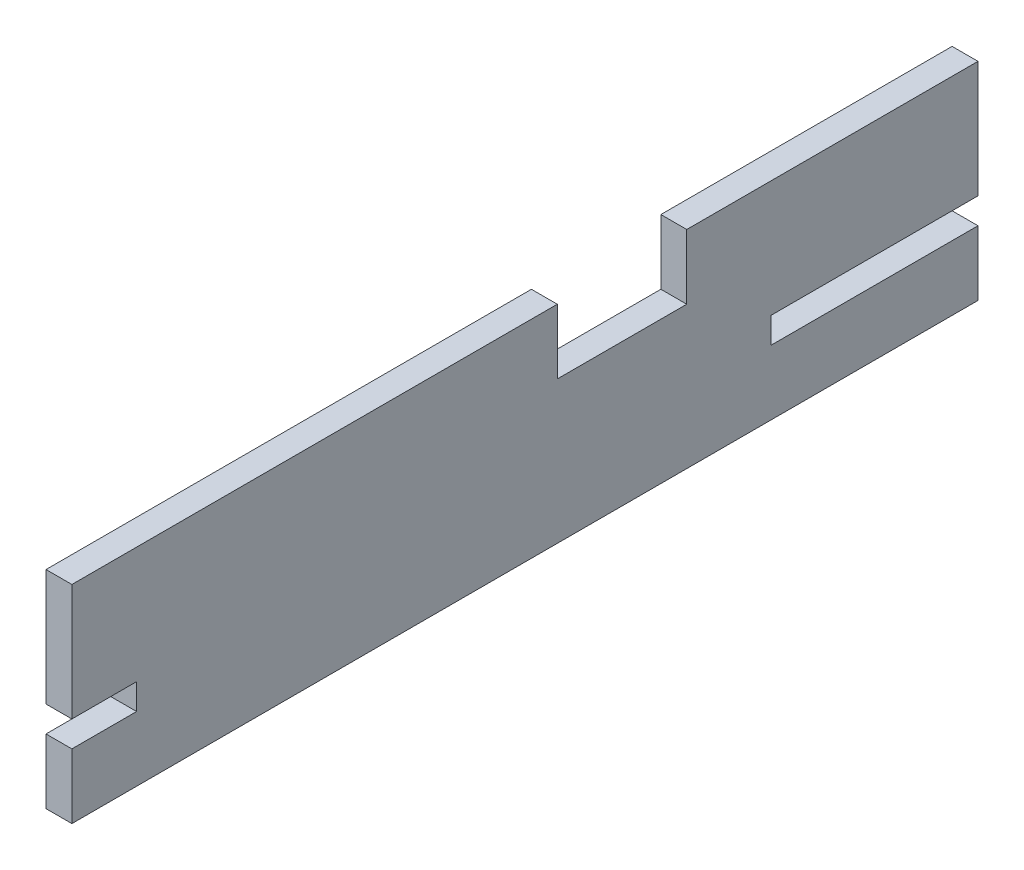
SolidWorks part; units mm, degrees
material "Pine"
ref_plane "Front Plane" through (0, 0, 0) normal (0, 0, 1) x (1, 0, 0)
ref_plane "Top Plane" through (0, 0, 0) normal (0, 1, 0) x (1, 0, 0)
ref_plane "Right Plane" through (0, 0, 0) normal (1, 0, 0) x (0, 0, -1)
sketch "Sketch1" plane through (0, 0, 0) normal (1, 0, 0) x (0, 0, -1)
  line L16 (-59.6816, 15.5612) -> (-59.6816, -2.4388)
  line L17 (-59.6816, -2.4388) -> (-49.6816, -2.4388)
  line L18 (-49.6816, -2.4388) -> (-49.6816, -6.4388)
  line L19 (-49.6816, -6.4388) -> (-59.6816, -6.4388)
  line L20 (-59.6816, -6.4388) -> (-59.6816, -16.4388)
  line L21 (-59.6816, -16.4388) -> (80.3184, -16.4388)
  line L22 (80.3184, -16.4388) -> (80.3184, -6.4388)
  line L23 (80.3184, -6.4388) -> (48.3184, -6.4388)
  line L24 (48.3184, -6.4388) -> (48.3184, -2.4388)
  line L25 (48.3184, -2.4388) -> (80.3184, -2.4388)
  line L26 (80.3184, -2.4388) -> (80.3184, 15.5612)
  line L29 (15.3184, 15.5612) -> (15.3184, 5.5612)
  line L30 (15.3184, 5.5612) -> (35.3184, 5.5612)
  line L31 (35.3184, 5.5612) -> (35.3184, 15.5612)
  line L32 (35.3184, 15.5612) -> (80.3184, 15.5612)
  line L33 (15.3184, 15.5612) -> (-59.6816, 15.5612)
  dimension "D2" = 4
  dimension "D3" = 45
  dimension "D4" = 10
  dimension "D5" = 20
  dimension "D11" = 18
  dimension "D12" = 10
  dimension "D13" = 10
  dimension "D15" = 32
  dimension "D16" = 140
extrude "Boss-Extrude1" add sketch "Sketch1" along normal blind 4
